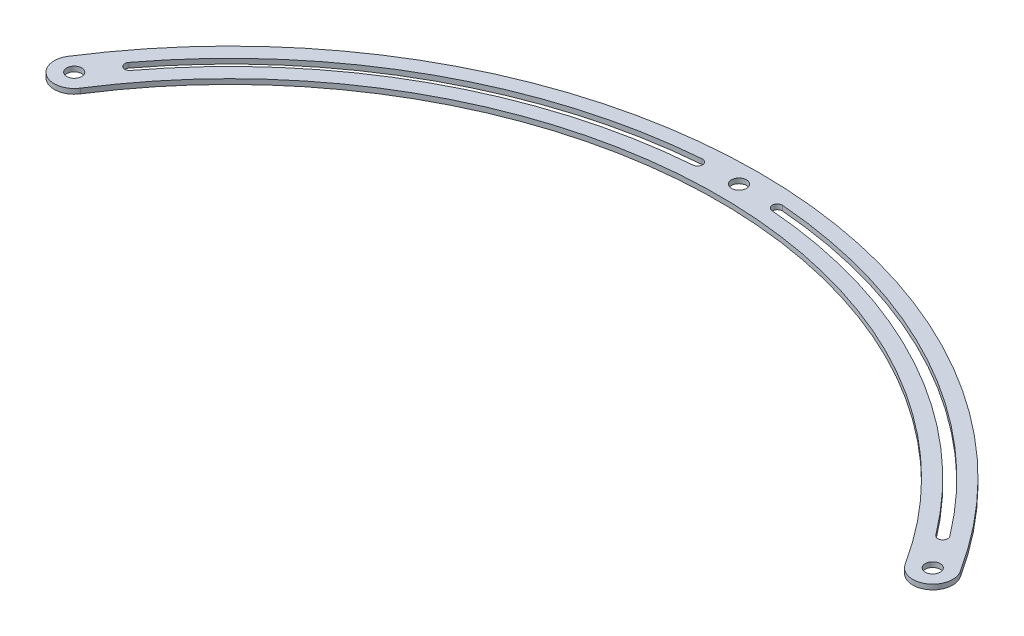
SolidWorks part; units mm, degrees
ref_plane "前视基准面" through (0, 0, 0) normal (0, 0, 1) x (1, 0, 0)
ref_plane "上视基准面" through (0, 0, 0) normal (0, 1, 0) x (1, 0, 0)
ref_plane "右视基准面" through (0, 0, 0) normal (1, 0, 0) x (0, 0, -1)
sketch "草图1" plane through (0, 0, 0) normal (0, 1, 0) x (1, 0, 0)
  circle A0 centre (0, 0) radius 102 construction
  circle A1 centre (0, 102) radius 1.5
  circle A2 centre (-86.0259, 54.8046) radius 1.5
  circle A3 centre (86.0259, 54.8046) radius 1.5
  arc A4 (-86.0259, 54.8046) -> (86.0259, 54.8046) centre (0, 0) cw construction
  arc A5 (89.3995, 56.9538) -> (-89.3995, 56.9538) centre (0, 0) ccw
  arc A6 (82.6524, 52.6554) -> (-82.6524, 52.6554) centre (0, 0) ccw
  arc A7 (82.6524, 52.6554) -> (89.3995, 56.9538) centre (86.0259, 54.8046) ccw
  arc A8 (-89.3995, 56.9538) -> (-82.6524, 52.6554) centre (-86.0259, 54.8046) ccw
  arc A9 (-81.4662, 61.3779) -> (-8, 101.6858) centre (0, 0) cw construction
  arc A10 (-8.0784, 102.6827) -> (-82.2649, 61.9797) centre (0, 0) ccw
  arc A11 (-7.9216, 100.6889) -> (-80.6676, 60.7762) centre (0, 0) ccw
  arc A12 (-7.9216, 100.6889) -> (-8.0784, 102.6827) centre (-8, 101.6858) ccw
  arc A13 (-82.2649, 61.9797) -> (-80.6676, 60.7762) centre (-81.4662, 61.3779) ccw
  arc A14 (8, 101.6858) -> (81.4662, 61.3779) centre (0, 0) cw construction
  arc A15 (82.2649, 61.9797) -> (8.0784, 102.6827) centre (0, 0) ccw
  arc A16 (80.6676, 60.7762) -> (7.9216, 100.6889) centre (0, 0) ccw
  arc A17 (80.6676, 60.7762) -> (82.2649, 61.9797) centre (81.4662, 61.3779) ccw
  arc A18 (8.0784, 102.6827) -> (7.9216, 100.6889) centre (8, 101.6858) ccw
  point P11 (0, 102)
  point P19 (-49.0636, 89.4246)
  point P24 (49.0636, 89.4246)
  point P32 (0, 0)
  dimension "D1" = 204
  dimension "D2" = 3
  dimension "D3" = 57.5
  dimension "D5" = 8
  dimension "D6" = 2
  dimension "D4" = 57.5
  dimension "D7" = 8
  dimension "D8" = 8
  dimension "D9" = 8
extrude "凸台-拉伸1" add sketch "草图1" along normal blind 1
